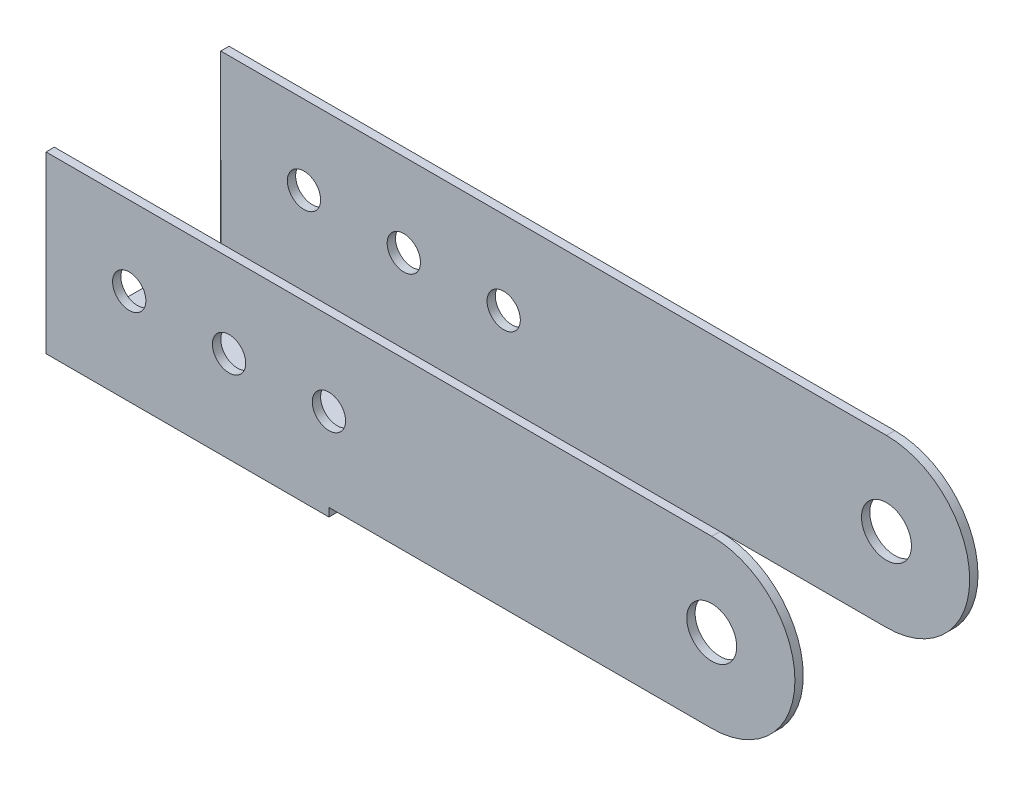
SolidWorks part; units mm, degrees
ref_plane "前视" through (0, 0, 0) normal (0, 0, 1) x (1, 0, 0)
ref_plane "上视" through (0, 0, 0) normal (0, 1, 0) x (1, 0, 0)
ref_plane "右视" through (0, 0, 0) normal (1, 0, 0) x (0, 0, -1)
sketch "草图1" plane through (0, 0, 0) normal (0, 0, 1) x (1, 0, 0)
  line L0 (-20, 13.6585) -> (-20, -13.1517) construction
  line L1 (-25, 5) -> (15, 5)
  line L2 (-25, 5) -> (-25, -5)
  line L3 (-25, -5) -> (15, -5)
  line L4 (-16.7978, 0) -> (28.1127, 0) construction
  line L7 (-14, 13.6585) -> (-14, -13.1517) construction
  line L8 (-8, 13.6585) -> (-8, -13.1517) construction
  arc A0 (15, -5) -> (15, 5) centre (15, 0) ccw
  circle A1 centre (15, 0) radius 1.5
  circle A2 centre (-20, 0.2534) radius 1
  circle A3 centre (-14, 0) radius 1
  circle A4 centre (-8, 0) radius 1
  point P0 (0, 0)
  dimension "D3" = 10
  dimension "D4" = 3
  dimension "D8" = 2
  dimension "D9" = 2
  dimension "D10" = 2
  dimension "D1" = 10
  dimension "D2" = 40
  dimension "D5" = 5
  dimension "D6" = 11
  dimension "D7" = 17
ref_plane "基准面1" through (0, 0, 10) normal (0, 0, 1) x (1, 0, 0)
sketch "草图2" plane through (0, 0, 10) normal (0, 0, 1) x (1, 0, 0)
  line L3 (15, 5) -> (-25, 5)
  line L4 (-25, -5) -> (15, -5)
  line L5 (-25, 5) -> (-25, -5)
  line L6 (15, 5) -> (-25, 5)
  line L7 (-25, -5) -> (15, -5)
  line L8 (-25, 5) -> (-25, -5)
  circle A1 centre (15, 0) radius 1.5
  circle A2 centre (15, 0) radius 1.5
  arc A3 (15, -5) -> (15, 5) centre (15, 0) ccw
  arc A4 (15, -5) -> (15, 5) centre (15, 0) ccw
  circle A5 centre (-8, 0) radius 1
  circle A6 centre (-8, 0) radius 1
  circle A7 centre (-14, 0) radius 1
  circle A8 centre (-14, 0) radius 1
  circle A9 centre (-20, 0.2534) radius 1
  circle A10 centre (-20, 0.2534) radius 1
  dimension "D1" = 0
  dimension "D2" = 0
  dimension "D3" = 0
  dimension "D4" = 0
  dimension "D5" = 0
extrude "凸台-拉伸1" add sketch "草图2" along normal blind 0.5
extrude "凸台-拉伸2" add sketch "草图1" against normal blind 0.5 separate body
ref_plane "基准面2" through (0, -5, 0) normal (0, -1, 0) x (-1, 0, 0)
sketch "草图3" plane through (0, -5, 0) normal (0, -1, 0) x (-1, 0, 0)
  line L0 (8, 0.5) -> (25, 0.5)
  line L1 (8, 0.5) -> (8, 0) construction
  line L2 (25, 0.5) -> (-15, 0.5) construction
  line L3 (25, 0.5) -> (25, -10.5)
  line L4 (25, -10.5) -> (8, -10.5)
  line L5 (8, -10.5) -> (8, -10) construction
  line L6 (25, -10.5) -> (-15, -10.5) construction
  line L7 (8, -10.5) -> (8, 0.5)
extrude "凸台-拉伸3" add sketch "草图3" along normal blind 0.5
